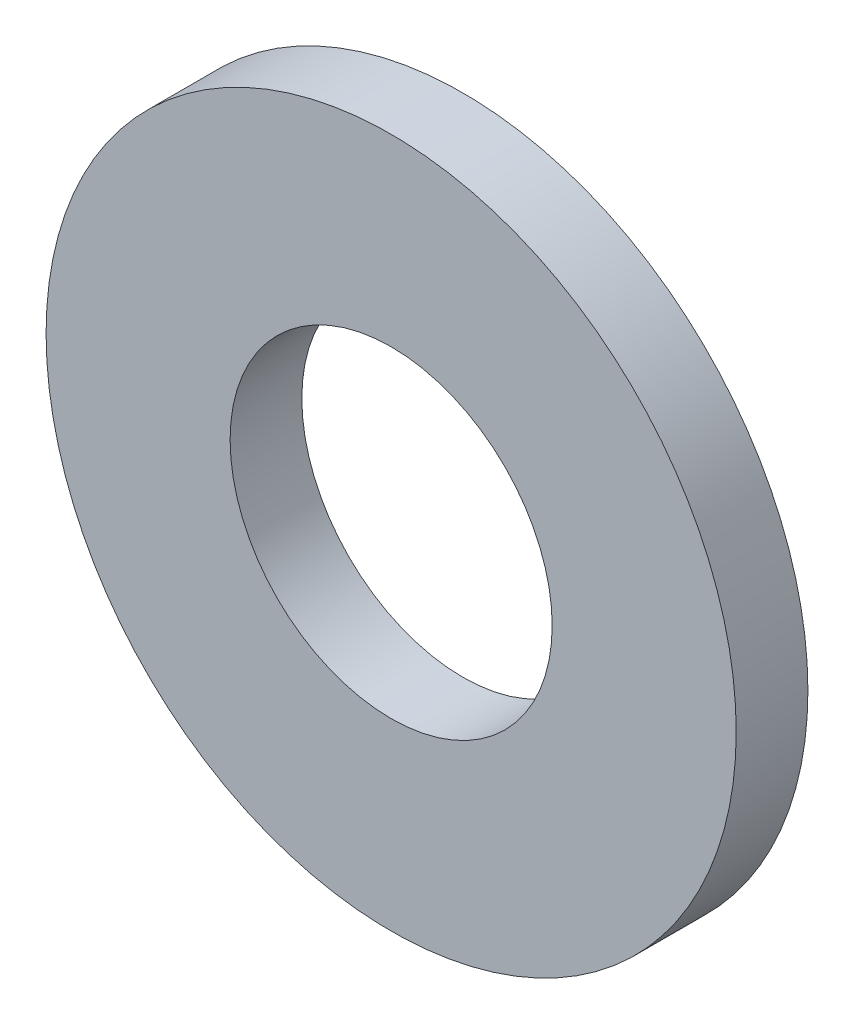
SolidWorks part; units mm, degrees
ref_plane "Front Plane" through (0, 0, 0) normal (0, 0, 1) x (1, 0, 0)
ref_plane "Top Plane" through (0, 0, 0) normal (0, 1, 0) x (1, 0, 0)
ref_plane "Right Plane" through (0, 0, 0) normal (1, 0, 0) x (0, 0, -1)
sketch "Sketch1" plane through (0, 0, 0) normal (0, 0, 1) x (1, 0, 0)
  circle A0 centre (0, 0) radius 4.2
  circle A1 centre (0, 0) radius 9
  dimension "ID" = 8.4
  dimension "OD" = 18
extrude "Extrude1" add sketch "Sketch1" against normal blind 1.87
